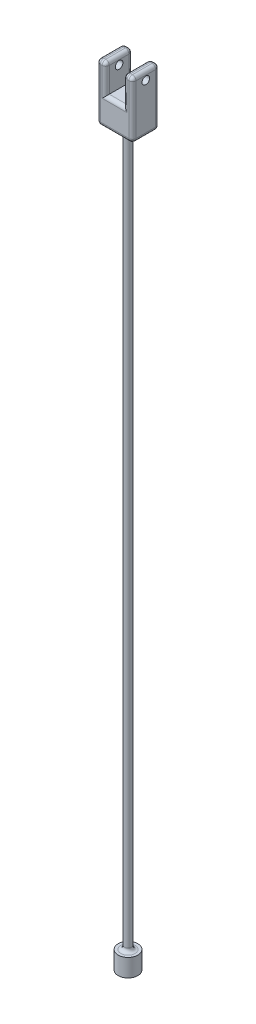
SolidWorks part; units mm, degrees
material "3003 Alloy"
ref_plane "Front Plane" through (0, 0, 0) normal (0, 0, 1) x (1, 0, 0)
ref_plane "Top Plane" through (0, 0, 0) normal (0, 1, 0) x (1, 0, 0)
ref_plane "Right Plane" through (0, 0, 0) normal (1, 0, 0) x (0, 0, -1)
sketch "Sketch1" plane through (0, 0, 0) normal (0, 1, 0) x (1, 0, 0)
  circle A0 centre (0, 0) radius 5.525
  dimension "D1" = 11.05
extrude "Cork/Stopper/VacummPump" add sketch "Sketch1" along normal blind 10
sketch "Sketch3" plane through (0, 10, 0) normal (0, 1, 0) x (1, 0, 0)
  circle A0 centre (0, 0) radius 2
  dimension "D1" = 4
extrude "LongThinShaft" add sketch "Sketch3" along normal blind 400
sketch "Sketch4" plane through (0, 410, 0) normal (0, 1, 0) x (1, 0, 0)
  line L1 (-10, -7.5) -> (10, -7.5)
  line L2 (-10, -7.5) -> (-10, 7.5)
  line L3 (-10, 7.5) -> (10, 7.5)
  line L4 (10, -7.5) -> (10, 7.5)
  line L5 (-10, -7.5) -> (10, 7.5) construction
  line L6 (-10, 7.5) -> (10, -7.5) construction
  point P0 (0, 0)
  dimension "D1" = 20
  dimension "D2" = 15
extrude "Boss-Extrude3" add sketch "Sketch4" along normal blind 32
sketch "Sketch5" plane through (0, 0, 7.5) normal (0, 0, 1) x (1, 0, 0)
  line L5 (-10, 442) -> (10, 442) construction
  line L6 (-5, 442) -> (5, 442)
  line L7 (-5, 442) -> (-5, 410)
  line L8 (-5, 410) -> (5, 410)
  line L9 (5, 442) -> (5, 410)
  line L10 (-10, 410) -> (10, 410) construction
  line L11 (10, 442) -> (10, 410) construction
  line L12 (-5, 426) -> (5, 426)
  dimension "D1" = 10
  dimension "D2" = 5
extrude "Cut-Extrude2" cut sketch "Sketch5" against normal up to next
sketch "Sketch7" plane through (-10, 0, 0) normal (-1, 0, 0) x (0, 0, 1)
  line L0 (0, 442) -> (0, 410) construction
  line L1 (-7.5, 442) -> (7.5, 442) construction
  line L2 (-2, 410) -> (2, 410) construction
  circle A0 centre (0, 437.5) radius 2.125
  dimension "D1" = 4.25
  dimension "D2" = 4.5
extrude "Cut-Extrude3" cut sketch "Sketch7" against normal blind 20
fillet "Fillet1" radius 2 1 edges at (0, 410, 2)
fillet "Fillet2" radius 2 22 edges at (-10, 442, 0) (-5, 442, 0) (10, 442, 0) (5, 442, 0) (-10, 426, -7.5) (0, 410, -7.5) (10, 426, -7.5) (7.5, 442, -7.5) (5, 434, -7.5) (0, 426, -7.5) (-5, 434, -7.5) (-7.5, 442, -7.5) (5, 434, 7.5) (7.5, 442, 7.5) (10, 426, 7.5) (0, 410, 7.5) (-10, 426, 7.5) (-7.5, 442, 7.5) (-5, 434, 7.5) (0, 426, 7.5) (-10, 410, 0) (10, 410, 0)
fillet "Fillet3" radius 2 1 edges at (0, 10, 2)
